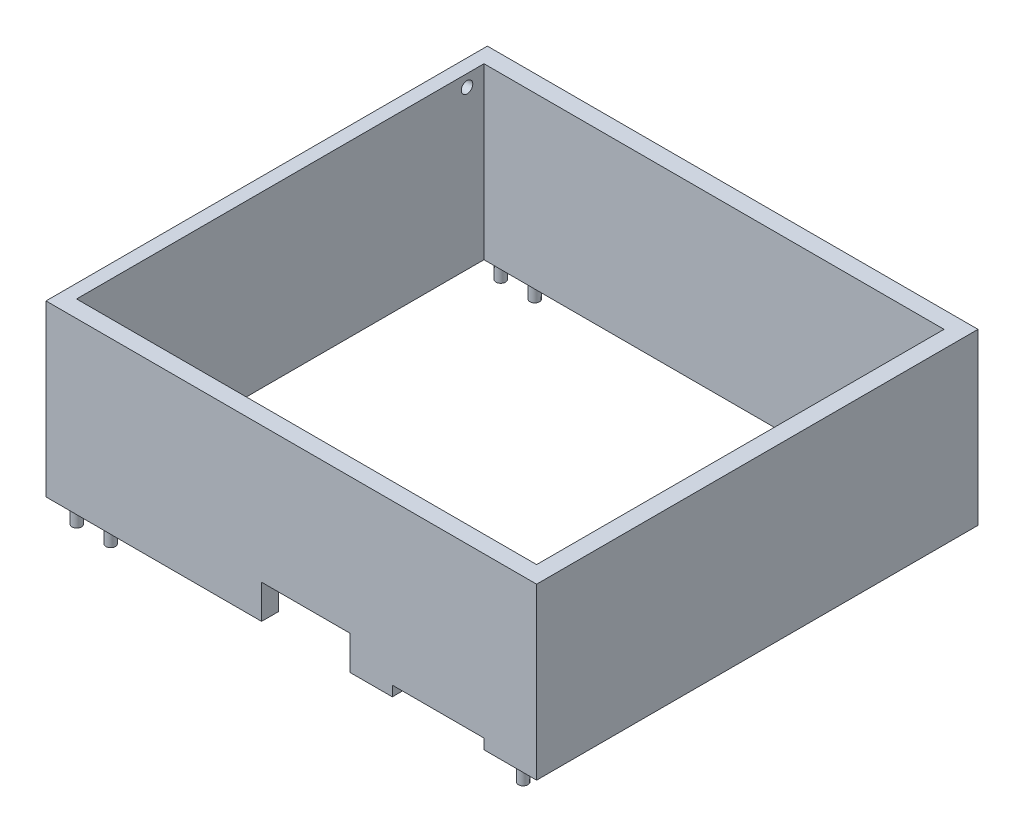
SolidWorks part; units mm, degrees
ref_plane "Front Plane" through (0, 0, 0) normal (0, 0, 1) x (1, 0, 0)
ref_plane "Top Plane" through (0, 0, 0) normal (0, 1, 0) x (1, 0, 0)
ref_plane "Right Plane" through (0, 0, 0) normal (1, 0, 0) x (0, 0, -1)
sketch "Sketch1" plane through (0, 0, 0) normal (0, 1, 0) x (1, 0, 0)
  line L1 (0, 0) -> (72.25, 0)
  line L4 (72.25, 0) -> (72.25, -65)
  line L7 (72.25, -65) -> (0, -65)
  line L12 (69.75, -2.5) -> (69.75, -62.5)
  line L14 (0, 0) -> (0, -65)
  line L15 (2, -2.5) -> (2, -62.5)
  line L16 (2, -2.5) -> (69.75, -2.5)
  line L17 (2, -62.5) -> (69.75, -62.5)
  point P0 (0, 0)
  dimension "D1" = 72.25
  dimension "D2" = 2.5
  dimension "D3" = 2.5
  dimension "D4" = 65
  dimension "D5" = 2.5
  dimension "D7" = 2
extrude "Boss-Extrude1" add sketch "Sketch1" along normal blind 25
sketch "Sketch2" plane through (0, 0, 65) normal (0, 0, 1) x (1, 0, 0)
  line L0 (0, 0) -> (72.25, 0) construction
  line L1 (31.75, 0) -> (44.75, 0)
  line L2 (31.75, 0) -> (31.75, 5)
  line L3 (31.75, 5) -> (44.75, 5)
  line L4 (44.75, 0) -> (44.75, 5)
  line L6 (72.25, 25) -> (72.25, 0) construction
  line L7 (51, 0) -> (64.5, 0)
  line L8 (51, 0) -> (51, 1.5)
  line L9 (51, 1.5) -> (64.5, 1.5)
  line L10 (64.5, 0) -> (64.5, 1.5)
  point P6 (49.1314, 5)
  point P7 (23.8769, 5)
  point P12 (46.0755, 1.5)
  point P13 (57.75, 0)
  point P16 (38.25, 0)
  dimension "D1" = 5
  dimension "D2" = 13
  dimension "D3" = 14.5
  dimension "D4" = 13.5
  dimension "D5" = 34
  dimension "D6" = 1.5
extrude "Cut-Extrude1" cut sketch "Sketch2" against normal up to surface (2.5 mm away) up to face at (35.875, 12.5, 62.5)
sketch "Sketch5" plane through (0, 0, 0) normal (0, -1, 0) x (1, 0, 0)
  line L2 (72.25, 32.5) -> (0, 32.5) construction
  line L3 (72.25, 65) -> (72.25, 0) construction
  line L4 (36.125, 0) -> (36.125, 65) construction
  line L5 (72.25, 0) -> (0, 0) construction
  line L6 (0, 65) -> (31.75, 65) construction
  circle A0 centre (3.25, 63.7221) radius 0.7
  circle A1 centre (8.25, 63.7221) radius 0.7
  circle A2 centre (3.25, 1.2779) radius 0.7
  circle A3 centre (8.25, 1.2779) radius 0.7
  circle A4 centre (69, 63.7221) radius 0.7
  circle A6 centre (69, 1.2779) radius 0.7
  circle A7 centre (64, 1.2779) radius 0.7
  point P4 (0, 0)
  point P5 (0, 0)
  point P9 (8.25, 63.7221)
  dimension "D1" = 1.4
  dimension "D2" = 1.4
  dimension "D4" = 1.25
  dimension "D3" = 5
extrude "Boss-Extrude2" add sketch "Sketch5" along normal blind 2.5
sketch "Sketch6" plane through (0, 25, 0) normal (0, 1, 0) x (1, 0, 0)
  line L0 (0, 0) -> (0, -65) construction
  line L1 (2, -8) -> (0, -8)
  line L2 (2, -8) -> (2, -57)
  line L3 (2, -57) -> (0, -57)
  line L4 (0, -8) -> (0, -57)
  line L5 (0, -65) -> (72.25, -65) construction
  line L6 (72.25, 0) -> (0, 0) construction
  line L7 (2, -2.5) -> (2, -62.5) construction
  point P7 (2, -62.5)
  point P9 (0, 0)
  point P10 (0, 0)
  dimension "D1" = 8
  dimension "D2" = 8
extrude "Cut-Extrude2" [suppressed] cut sketch "Sketch6" against normal blind 12
sketch "Sketch7" plane through (69.75, 0, 0) normal (-1, 0, 0) x (0, 0, 1)
  line L0 (2.5, 25) -> (2.5, 0) construction
  line L1 (62.5, 25) -> (2.5, 25) construction
  circle A0 centre (5, 23.25) radius 0.85
  dimension "D3" = 1.7
  dimension "D1" = 2.5
  dimension "D2" = 1.75
extrude "Cut-Extrude3" cut sketch "Sketch7" against normal blind 1.25
sketch "Sketch8" plane through (2, 0, 0) normal (1, 0, 0) x (0, 0, -1)
  circle A1 centre (-5, 23.25) radius 0.85
  circle A2 centre (-5, 23.25) radius 0.85
  dimension "D1" = 0
extrude "Cut-Extrude4" cut sketch "Sketch8" against normal blind 1.25
